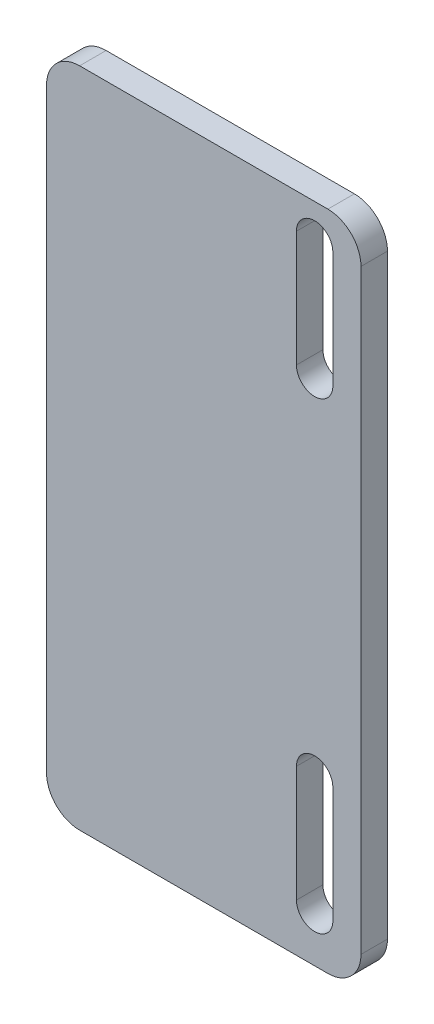
SolidWorks part; units mm, degrees
ref_plane "Спереди" through (0, 0, 0) normal (0, 0, 1) x (1, 0, 0)
ref_plane "Сверху" through (0, 0, 0) normal (0, 1, 0) x (1, 0, 0)
ref_plane "Справа" through (0, 0, 0) normal (1, 0, 0) x (0, 0, -1)
sketch "Эскиз1" plane through (0, 0, 0) normal (0, 0, 1) x (1, 0, 0)
  line L1 (0, 0) -> (19, 0)
  line L2 (0, 0) -> (0, 40)
  line L3 (0, 40) -> (19, 40)
  line L4 (19, 0) -> (19, 40)
  dimension "D1" = 19
  dimension "D2" = 40
extrude "Бобышка-Вытянуть1" add sketch "Эскиз1" along normal blind 1.6
fillet "Скругление1" radius 2 4 edges at (19, 0, 0.8) (0, 0, 0.8) (0, 40, 0.8) (19, 40, 0.8)
sketch "Эскиз3" plane through (0, 0, 1.6) normal (0, 0, 1) x (1, 0, 0)
  line L0 (16.2, 2.8934) -> (16.2, 9.8934) construction
  line L1 (17, 6.3934) -> (15.4, 6.3934) construction
  line L2 (17, 9.8934) -> (17, 2.8934) construction
  line L3 (15.4, 9.8934) -> (15.4, 2.8934) construction
  line L4 (15.1, 2.8934) -> (15.1, 9.8934)
  line L5 (17.3, 2.8934) -> (17.3, 9.8934)
  line L6 (17, 34.3934) -> (15.4, 34.3934) construction
  line L7 (17, 37.8934) -> (17, 30.8934) construction
  line L8 (15.4, 37.8934) -> (15.4, 30.8934) construction
  line L9 (16.2, 30.8934) -> (16.2, 37.8934) construction
  line L10 (15.1, 30.8934) -> (15.1, 37.8934)
  line L11 (17.3, 30.8934) -> (17.3, 37.8934)
  arc A0 (15.1, 2.8934) -> (17.3, 2.8934) centre (16.2, 2.8934) ccw
  arc A1 (17.3, 9.8934) -> (15.1, 9.8934) centre (16.2, 9.8934) ccw
  arc A2 (15.1, 30.8934) -> (17.3, 30.8934) centre (16.2, 30.8934) ccw
  arc A3 (17.3, 37.8934) -> (15.1, 37.8934) centre (16.2, 37.8934) ccw
  point P6 (16.2, 6.3934)
  point P21 (16.2, 34.3934)
  dimension "D1" = 2.2
  dimension "D2" = 7
  dimension "D3" = 2.2
  dimension "D4" = 7
extrude "Вырез-Вытянуть1" cut sketch "Эскиз3" against normal through all
